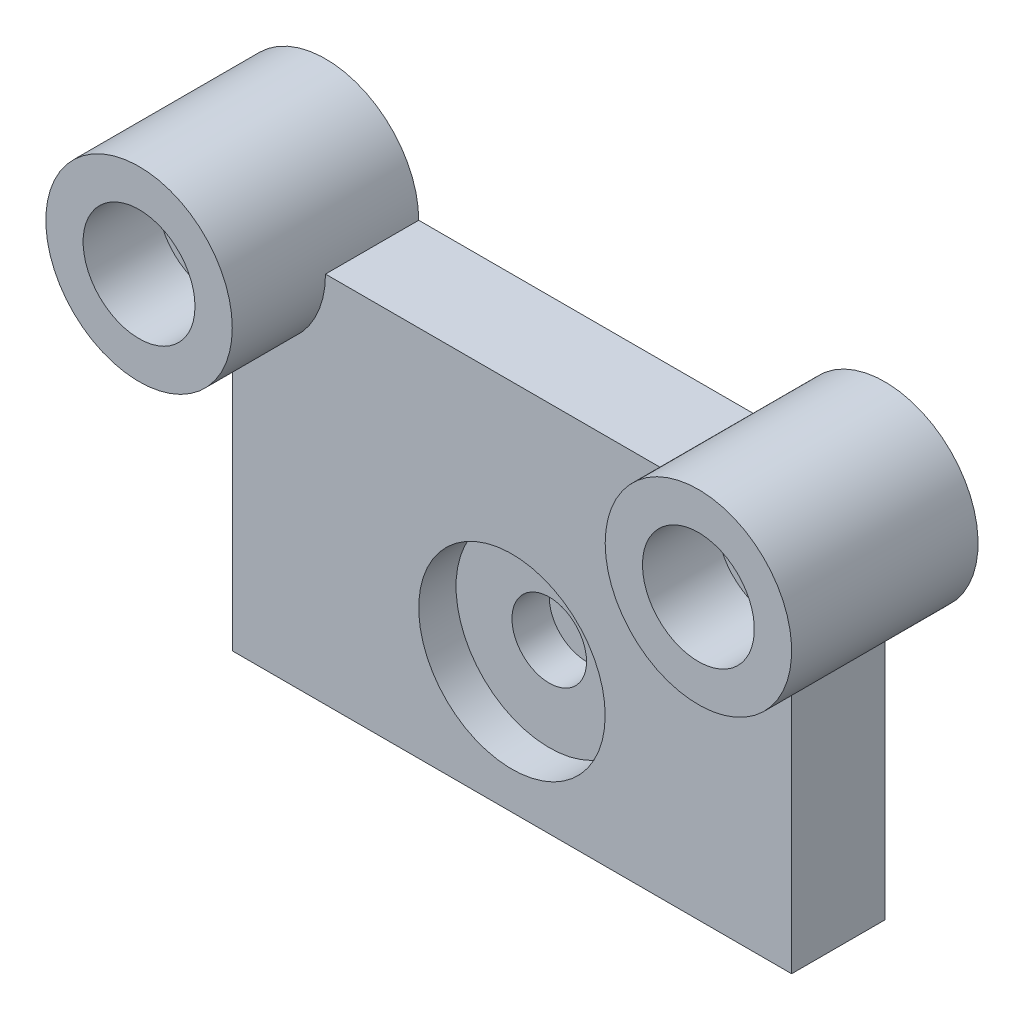
SolidWorks part; units mm, degrees
ref_plane "Спереди" through (0, 0, 0) normal (0, 0, 1) x (1, 0, 0)
ref_plane "Сверху" through (0, 0, 0) normal (0, 1, 0) x (1, 0, 0)
ref_plane "Справа" through (0, 0, 0) normal (1, 0, 0) x (0, 0, -1)
sketch "Эскиз1" plane through (0, 0, 0) normal (0, 0, 1) x (1, 0, 0)
  line L1 (0, 0) -> (150, 0)
  line L2 (0, 0) -> (0, -100)
  line L3 (0, -100) -> (150, -100)
  line L4 (150, 0) -> (150, -100)
  dimension "D1" = 150
  dimension "D2" = 100
extrude "Бобышка-Вытянуть1" add sketch "Эскиз1" along normal blind 25
sketch "Эскиз2" plane through (0, 0, 25) normal (0, 0, 1) x (1, 0, 0)
  line L0 (75, 0) -> (75, -100) construction
  line L1 (150, 0) -> (0, 0) construction
  line L2 (0, -100) -> (150, -100) construction
  circle A0 centre (0, 0) radius 25
  circle A1 centre (150, 0) radius 25
  dimension "D1" = 50
extrude "Бобышка-Вытянуть2" add sketch "Эскиз2" along normal mid plane 50
sketch "Эскиз3" plane through (0, 0, 50) normal (0, 0, 1) x (1, 0, 0)
  line L0 (75, 0) -> (75, -100) construction
  line L1 (125, 0) -> (25, 0) construction
  line L2 (0, -100) -> (150, -100) construction
  circle A0 centre (0, 0) radius 15
  circle A1 centre (150, 0) radius 15
  dimension "D1" = 30
extrude "Вырез-Вытянуть1" cut sketch "Эскиз3" against normal blind 20
sketch "Эскиз4" plane through (0, 0, 30) normal (0, 0, 1) x (1, 0, 0)
  line L0 (75, 0) -> (75, -100) construction
  line L1 (125, 0) -> (25, 0) construction
  line L2 (0, -100) -> (150, -100) construction
  circle A0 centre (0, 0) radius 7.5
  circle A1 centre (150, 0) radius 7.5
  dimension "D1" = 15
extrude "Вырез-Вытянуть2" cut sketch "Эскиз4" against normal blind 15
sketch "Эскиз5" plane through (0, 0, 25) normal (0, 0, 1) x (1, 0, 0)
  line L0 (75, 0) -> (75, -100)
  line L1 (125, 0) -> (25, 0) construction
  line L2 (0, -100) -> (150, -100) construction
  circle A0 centre (75, -65) radius 25
  point P8 (75, -67.4319)
  point P9 (75, -64.8754)
  dimension "D1" = 50
  dimension "D2" = 35
extrude "Вырез-Вытянуть3" cut sketch "Эскиз5" against normal blind 10 contours L0 A0 | L0 A0
sketch "Эскиз6" plane through (0, 0, 15) normal (0, 0, 1) x (1, 0, 0)
  circle A0 centre (75, -65) radius 10
  dimension "D1" = 20
extrude "Вырез-Вытянуть4" cut sketch "Эскиз6" against normal blind 10
